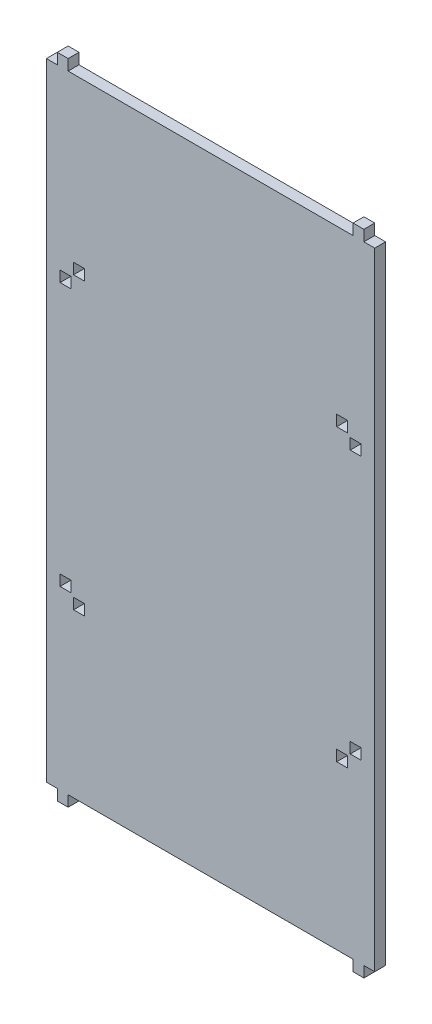
SolidWorks part; units mm, degrees
ref_plane "Front Plane" through (0, 0, 0) normal (0, 0, 1) x (1, 0, 0)
ref_plane "Top Plane" through (0, 0, 0) normal (0, 1, 0) x (1, 0, 0)
ref_plane "Right Plane" through (0, 0, 0) normal (1, 0, 0) x (0, 0, -1)
sketch "Sketch1" plane through (0, 0, 0) normal (0, 0, 1) x (1, 0, 0)
  line L0 (0, -55) -> (0, 55) construction
  line L1 (-23.3, 49.275) -> (23.3, 49.275)
  line L2 (-23.3, 49.275) -> (-23.3, -49.275)
  line L3 (-23.3, -49.275) -> (23.3, -49.275)
  line L4 (23.3, 49.275) -> (23.3, -49.275)
  line L5 (55, 0) -> (-55, 0) construction
  point P5 (0, 49.275)
  point P8 (23.3, 0)
  dimension "D1" = 98.55
  dimension "D2" = 46.6
extrude "Boss-Extrude1" add sketch "Sketch1" along normal blind 1.65
sketch "Sketch3" plane through (-23.3, 0, 0) normal (-1, 0, 0) x (0, 0, 1)
  line L0 (1.65, 49.275) -> (1.65, -49.275) construction
  line L1 (1.65, 47.625) -> (0, 47.625)
  line L2 (1.65, 47.625) -> (1.65, -47.625)
  line L3 (1.65, -47.625) -> (0, -47.625)
  line L4 (0, 47.625) -> (0, -47.625)
  line L5 (0, 49.275) -> (0, -49.275) construction
  line L6 (1.65, -49.275) -> (0, -49.275) construction
  line L7 (1.65, 49.275) -> (0, 49.275) construction
  dimension "D1" = 1.65
  dimension "D2" = 1.65
extrude "Boss-Extrude2" add sketch "Sketch3" along normal blind 1.65
mirror "Mirror1" about plane through (0, 0, 0) normal (1, 0, 0) of "Boss-Extrude2"
sketch "Sketch2" plane through (0, 0, 1.65) normal (0, 0, 1) x (1, 0, 0)
  line L0 (0.9075, 0) -> (-0.9075, 0) construction
  line L1 (21.225, 20.825) -> (22.875, 20.825)
  line L2 (21.225, 20.825) -> (21.225, -20.825)
  line L3 (21.225, -20.825) -> (22.875, -20.825)
  line L4 (22.875, 20.825) -> (22.875, -20.825)
  line L5 (22.875, -20.825) -> (21.225, -19.175) construction
  line L7 (20.825, -21.225) -> (20.825, -22.875)
  line L8 (20.825, -21.225) -> (-20.825, -21.225)
  line L9 (-20.825, -21.225) -> (-20.825, -22.875)
  line L10 (20.825, -22.875) -> (-20.825, -22.875)
  line L11 (-21.225, -20.825) -> (-22.875, -20.825)
  line L12 (-21.225, -20.825) -> (-21.225, 20.825)
  line L13 (-21.225, 20.825) -> (-22.875, 20.825)
  line L14 (-22.875, -20.825) -> (-22.875, 20.825)
  line L15 (-20.825, 21.225) -> (-20.825, 22.875)
  line L16 (-20.825, 21.225) -> (20.825, 21.225)
  line L17 (20.825, 21.225) -> (20.825, 22.875)
  line L18 (-20.825, 22.875) -> (20.825, 22.875)
  line L19 (21.225, 19.175) -> (22.875, 19.175)
  line L20 (21.225, -19.175) -> (22.875, -19.175)
  line L21 (-19.175, -21.225) -> (-19.175, -22.875)
  line L22 (19.175, -21.225) -> (19.175, -22.875)
  line L23 (-21.225, 19.175) -> (-22.875, 19.175)
  line L24 (-21.225, -19.175) -> (-22.875, -19.175)
  line L25 (19.175, 21.225) -> (19.175, 22.875)
  line L26 (-19.175, 21.225) -> (-19.175, 22.875)
  line L27 (22.875, 20.825) -> (21.225, 19.175) construction
  line L28 (22.875, 19.175) -> (21.225, 20.825) construction
  line L29 (22.875, -19.175) -> (21.225, -20.825) construction
  line L30 (0, -0.9075) -> (0, 0.9075) construction
  point P4 (22.875, 0)
  point P10 (22.05, -20)
  point P26 (22.05, 20)
  dimension "D1" = 1.65
  dimension "D5" = 1.65
  dimension "D6" = 1.65
  dimension "D3" = 22.05
  dimension "D2" = 40
  dimension "D4" = 4
  dimension "D7" = 4
extrude "Cut-Extrude1" cut sketch "Sketch2" against normal blind 1.65 contours L8 L22 L10 L7 | L21 L8 L9 L10 | L12 L24 L14 L11 | L23 L12 L13 L14 | L16 L26 L18 L15 | L25 L16 L17 L18 | L2 L19 L4 L1 | L20 L2 L3 L4
sketch "Sketch4" plane through (0, -49.275, 0) normal (0, -1, 0) x (1, 0, 0)
  line L0 (-23.3, 1.65) -> (23.3, 1.65) construction
  line L1 (-21.65, 1.65) -> (21.65, 1.65)
  line L2 (-21.65, 1.65) -> (-21.65, 0)
  line L3 (-21.65, 0) -> (21.65, 0)
  line L4 (21.65, 1.65) -> (21.65, 0)
  line L5 (-23.3, 0) -> (23.3, 0) construction
  line L6 (23.3, 0) -> (23.3, 1.65) construction
  line L7 (-23.3, 1.65) -> (-23.3, 0) construction
  dimension "D1" = 1.65
  dimension "D2" = 1.65
extrude "Cut-Extrude2" cut sketch "Sketch4" against normal blind 1.65
mirror "Mirror2" about plane through (0, 0, 0) normal (0, 1, 0) of "Cut-Extrude2"
equation "\"D1@Sketch1\"=3/8 * \"lenght\" + \"PCB Thickness\" * 2"
equation "\"Dinoskin scale\"= 1.8"
equation "\"pattern X\"= 3"
equation "\"Pattern Y\"= 9"
equation "\"Base Innerline\"= 0.34"
equation "\"lenght\"= 254"
equation "\"PCB Thickness\"= 1.65"
equation "\"Base Width\"= 4.5"
equation "\"Base Outerline\"= 1"
equation "\"Base Inner to Outer\"= 1"
equation "\"Dinoskin Outerline\"= \"Base Outerline\" * \"Dinoskin scale\""
equation "\"Dinoskin Innerline\"= \"Base Innerline\" * \"Dinoskin scale\""
equation "\"Dinoskin Width\"= \"Base Width\" * \"Dinoskin scale\""
equation "\"Dinoskin Inner to Outer\"= \"Base Inner to Outer\" * \"Dinoskin scale\""
equation "\"Diagonal dist\"= \"Dinoskin Width\" + ( ( \"Dinoskin Innerline\" + \"Dinoskin Outerline\" ) / 2 + \"Dinoskin Inner to Outer\" ) / cos ( 30 )"
equation "\"Dinoskin pattern Y\"= \"Diagonal dist\" * sin ( 30 )"
equation "\"Offset Y\"= 2 * \"Dinoskin pattern Y\""
equation "\"Diagonal dist 2\"= \"Dinoskin Width\" + ( ( \"Dinoskin Innerline\" + \"Dinoskin Outerline\" ) / 2 + 1 ) / cos ( 30 )"
equation "\"Dinoskin pattern X\"= \"Diagonal dist\" * cos ( 30 )"
equation "\"offset x\"= \"Dinoskin pattern X\" * 2"
equation "\"Pattern spacing X\"= \"offset x\" * ( \"pattern X\" - 0.5 ) / 2"
equation "\"Pattern spacing Y\"= \"Offset Y\" *  ( \"Pattern Y\" - 0.5 )  / 2 + 13"
equation "\"offset corner beams\" = 1"
equation "\"D2@Sketch1\"=40+  \"PCB Thickness\" * 4"
equation "\"D1@Boss-Extrude1\"= \"PCB Thickness\""
equation "\"D1@Sketch2\"= \"PCB Thickness\""
equation "\"D1@Sketch3\"= \"PCB Thickness\""
equation "\"D2@Sketch3\"=\"PCB Thickness\""
equation "\"D1@Boss-Extrude2\"=\"PCB Thickness\""
equation "\"D5@Sketch2\"= \"PCB Thickness\""
equation "\"D6@Sketch2\"=\"PCB Thickness\""
equation "\"D1@Sketch4\"= \"PCB Thickness\""
equation "\"D2@Sketch4\"= \"PCB Thickness\""
equation "\"D1@Cut-Extrude2\"= \"PCB Thickness\""
equation "\"D3@Sketch2\"=20 + 0.4 +\"PCB Thickness\""
